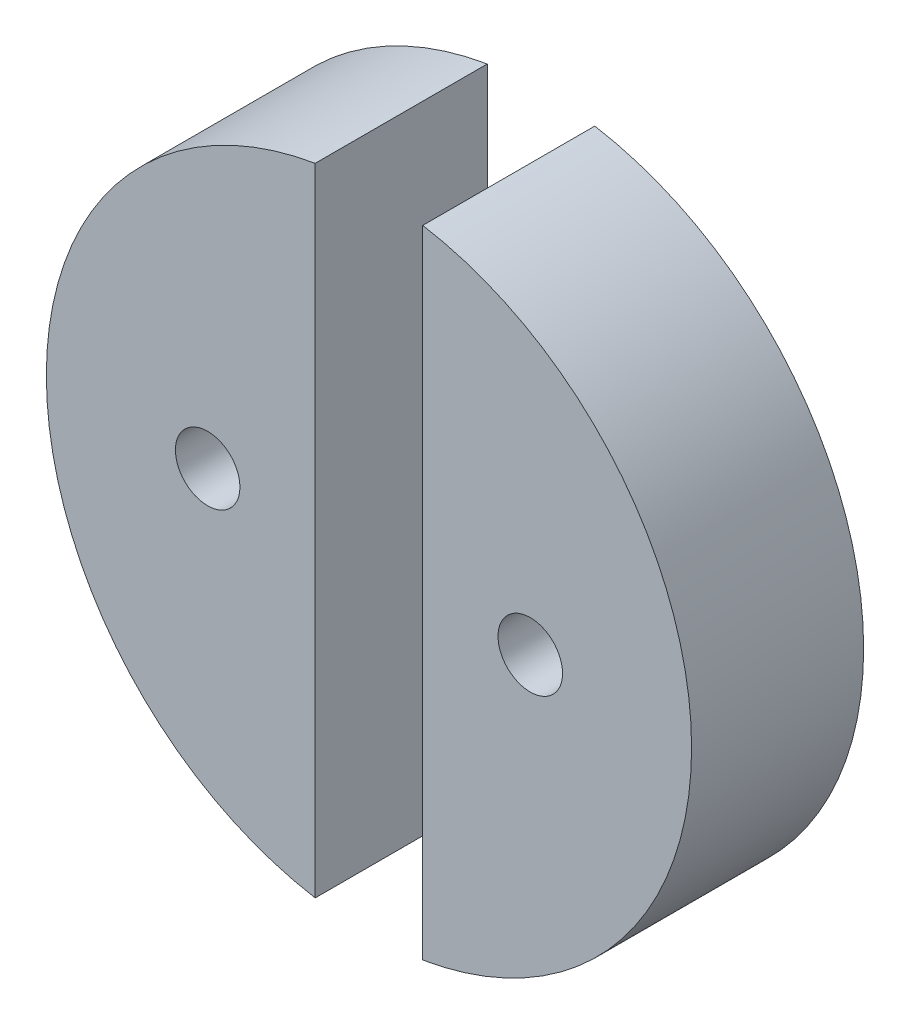
SolidWorks part; units mm, degrees
ref_plane "Front Plane" through (0, 0, 0) normal (0, 0, 1) x (1, 0, 0)
ref_plane "Top Plane" through (0, 0, 0) normal (0, 1, 0) x (1, 0, 0)
ref_plane "Right Plane" through (0, 0, 0) normal (1, 0, 0) x (0, 0, -1)
sketch "Sketch1" plane through (0, 0, 0) normal (0, 0, 1) x (1, 0, 0)
  line L0 (2.5, 0) -> (2.5, -14.7902)
  line L1 (2.5, 0) -> (2.5, 14.7902)
  line L2 (-2.5, 0) -> (-2.5, -14.7902)
  line L3 (-2.5, 0) -> (-2.5, 14.7902)
  arc A0 (2.5, -14.7902) -> (2.5, 14.7902) centre (0, 0) ccw
  arc A1 (-2.5, 14.7902) -> (-2.5, -14.7902) centre (0, 0) ccw
  circle A2 centre (7.5, 0) radius 1.5
  circle A3 centre (-7.5, 0) radius 1.5
extrude "Boss-Extrude1" add sketch "Sketch1" along normal blind 8
